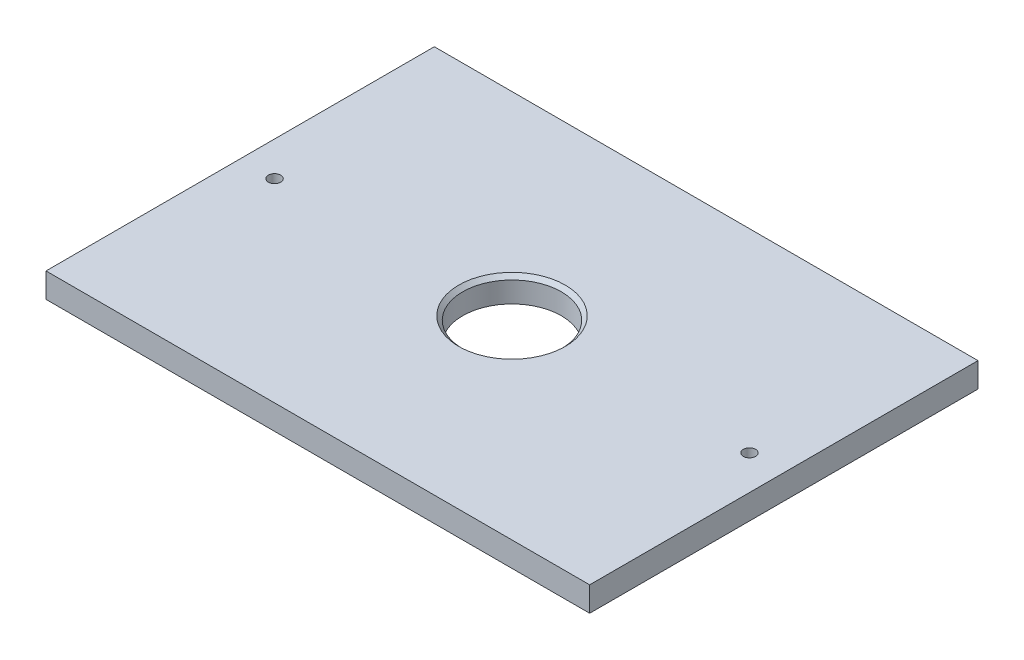
SolidWorks part; units mm, degrees
material "Oak"
ref_plane "Front Plane" through (0, 0, 0) normal (0, 0, 1) x (1, 0, 0)
ref_plane "Top Plane" through (0, 0, 0) normal (0, 1, 0) x (1, 0, 0)
ref_plane "Right Plane" through (0, 0, 0) normal (1, 0, 0) x (0, 0, -1)
sketch "Sketch1" plane through (0, 0, 0) normal (0, 1, 0) x (1, 0, 0)
  line L1 (0, 0) -> (140, 0)
  line L2 (0, 0) -> (0, 100)
  line L3 (0, 100) -> (140, 100)
  line L4 (140, 0) -> (140, 100)
  dimension "D1" = 140
  dimension "D2" = 100
extrude "Boss-Extrude1" add sketch "Sketch1" along normal blind 6.35
sketch "Sketch2" plane through (0, 6.35, 0) normal (0, 1, 0) x (1, 0, 0)
  line L0 (70, 100) -> (70, 0) construction
  line L1 (140, 100) -> (0, 100) construction
  line L2 (0, 0) -> (140, 0) construction
  line L3 (0, 50) -> (140, 50) construction
  line L4 (0, 100) -> (0, 0) construction
  line L5 (140, 0) -> (140, 100) construction
  circle A0 centre (70, 50) radius 12.705
  dimension "D1" = 25.41
extrude "Cut-Extrude1" cut sketch "Sketch2" against normal blind 10
sketch "Sketch3" plane through (0, 6.35, 0) normal (0, 1, 0) x (1, 0, 0)
  line L0 (0, 100) -> (0, 0) construction
  line L1 (140, 0) -> (140, 100) construction
  circle A0 centre (8.85, 50) radius 1.5875
  circle A1 centre (131.15, 50) radius 1.5875
  point P0 (0, 100)
  point P1 (0, 50)
  point P3 (8.85, 50)
  point P6 (131.15, 50)
  point P13 (0, 0)
  dimension "D1" = 3.175
  dimension "D2" = 3.175
  dimension "D3" = 8.85
  dimension "D4" = 8.85
extrude "Cut-Extrude2" cut sketch "Sketch3" against normal blind 10
chamfer "Chamfer1" distance 1 angle 45 1 edges at (70, 6.35, -37.295)
